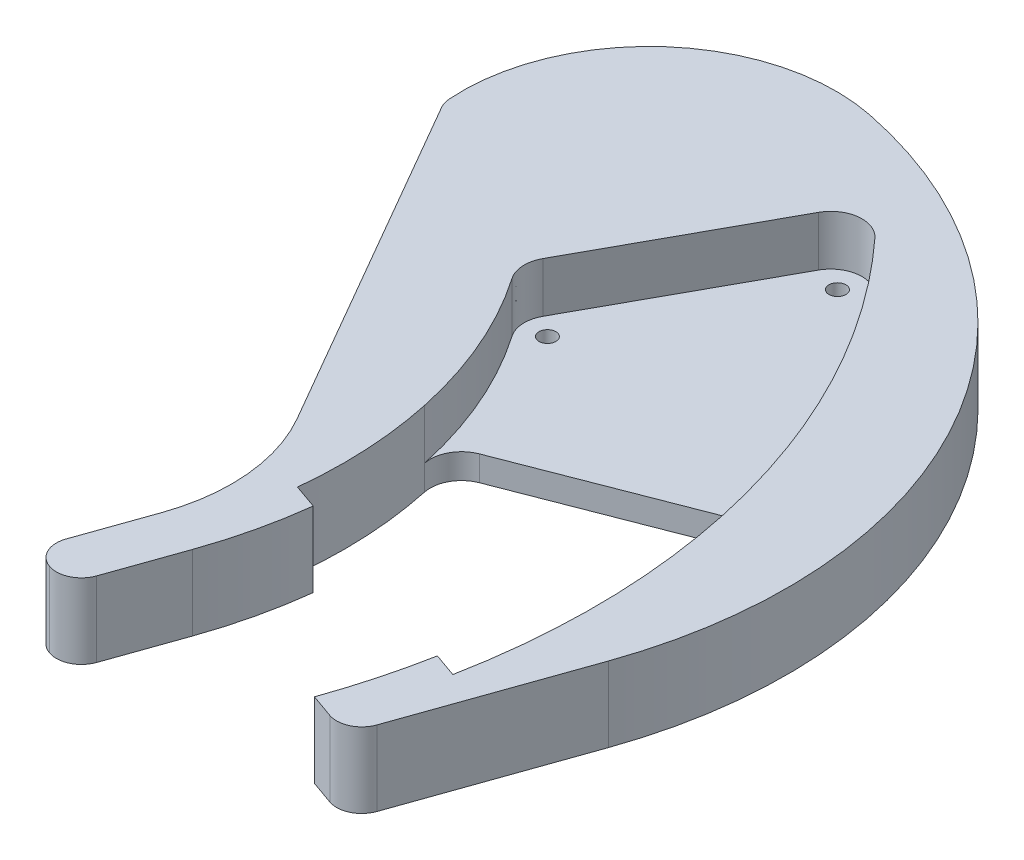
SolidWorks part; units mm, degrees
material "Pine"
ref_plane "Front Plane" through (0, 0, 0) normal (0, 0, 1) x (1, 0, 0)
ref_plane "Top Plane" through (0, 0, 0) normal (0, 1, 0) x (1, 0, 0)
ref_plane "Right Plane" through (0, 0, 0) normal (1, 0, 0) x (0, 0, -1)
sketch "Sketch1" plane through (0, 0, 0) normal (0, 1, 0) x (1, 0, 0)
  line L59 (-47.4532, 53.4043) -> (-98.2532, 141.3925)
  line L60 (0, 0) -> (27.9445, -9.8615)
  line L61 (0, 0) -> (-43.9505, 15.5099)
  line L62 (-1000, 0) -> (49000, 0) construction
  line L64 (27.9445, -9.8615) -> (72.8551, -25.7103) construction
  line L65 (72.8551, -25.7103) -> (88.7038, 19.2003) construction
  line L66 (27.9445, -9.8615) -> (-207.1917, -676.1663) construction
  line L67 (45.3803, 39.5461) -> (27.9445, -9.8615)
  line L68 (-43.9505, 15.5099) -> (-28.1017, 60.4205) construction
  line L69 (-88.861, 31.3587) -> (-86.5095, 38.0222) construction
  line L70 (53.7407, 188.0768) -> (-24.6782, 188.0768) construction
  line L71 (-43.9505, 15.5099) -> (-88.861, 31.3587) construction
  arc A0 (45.3803, 39.5461) -> (-41.5665, 192.8393) centre (-64.7226, 78.401) ccw
  arc A1 (-98.2532, 141.3925) -> (-41.5665, 192.8393) centre (-50.9898, 146.2689) cw
  arc A2 (-43.9505, 15.5099) -> (-47.4532, 53.4043) centre (-86.8603, 30.6526) ccw
  dimension "D5" = 4.7625
  dimension "D2" = 45.5033
  dimension "D11" = 37.8944
  dimension "D12" = 7.0663
  dimension "D8" = 52.3939
  dimension "D9" = 46.6069
  dimension "D4" = 19.438
  dimension "D7" = 116.7576
  dimension "D6" = 47.5143
  dimension "D10" = 29.6335
  dimension "D3" = 101.6
  dimension "D1" = 47.625
  dimension "D13" = 78.4189
extrude "Boss-Extrude1" add sketch "Sketch1" along normal blind 19.05
ref_plane "Plane1" through (-8.003, 0, -2.8242) normal (0.943, 0, 0.3328) x (0.3328, 0, -0.943)
sketch "Sketch2" plane through (0, 0, 0) normal (0, 1, 0) x (1, 0, 0)
  line L0 (-43.9505, 15.5099) -> (27.9445, -9.8615) construction
  point P2 (-8.003, 2.8242)
  point P3 (-8.003, 2.8242)
  line B0 (-29.2366, 81.4276) -> (15.5744, 98.7927)
  line B1 (11.6131, 92.147) -> (-21.6985, 79.2205)
  line B2 (-25.5648, 59.5252) -> (22.719, 42.4861)
  line B3 (28.6163, 16.8366) -> (22.5595, 18.974)
  line B4 (-26.1738, 36.1718) -> (-32.322, 38.3415)
  line B5 (-25.1489, 88.1192) -> (10.3796, 101.8872)
  line B6 (-51.3926, 119.7839) -> (-26.6046, 164.8774)
  line B7 (-44.0739, 123.2114) -> (-25.3, 157.3642)
  line B8 (-31.9553, 11.2769) -> (15.9493, -5.6285)
  line B9 (22.5595, 18.974) -> (-26.1738, 36.1718)
  arc B10 (-27.5994, 72.1341) -> (-28.8269, 77.6086) centre (-28.1238, 74.8914) ccw
  arc B11 (-29.2366, 81.4276) -> (-29.7842, 81.1914) centre (-26.3685, 74.0264) ccw
  arc B12 (17.8172, 99.3043) -> (15.5744, 98.7927) centre (18.4425, 91.3914) ccw
  arc B13 (18.8456, 95.8956) -> (20.3121, 90.5015) centre (19.3312, 93.1313) ccw
  arc B14 (13.6735, 91.1895) -> (20.9914, 87.3846) centre (19.3312, 93.1313) ccw
  arc B15 (-27.0229, 69.0118) -> (-22.587, 77.1552) centre (-28.1238, 74.8914) ccw
  arc B16 (20.3121, 90.5015) -> (18.8456, 95.8956) centre (19.3312, 93.1313) ccw
  arc B17 (28.6163, 16.8366) -> (26.1201, 93.4056) centre (-140.6727, 49.6428) ccw
  arc B18 (26.9496, 45.3998) -> (22.9664, 86.2145) centre (-140.6737, 49.643) ccw
  arc B19 (-28.827, 77.6085) -> (-27.5994, 72.1341) centre (-28.1238, 74.8914) ccw
  arc B20 (-27.6639, 62.1695) -> (-25.8173, 59.6267) centre (-24.5082, 62.5193) ccw
  arc B21 (-32.322, 38.3415) -> (-34.1314, 72.3702) centre (-140.6727, 49.6428) ccw
  arc B22 (10.3796, 101.8872) -> (14.8753, 112.2511) centre (7.5115, 109.2884) ccw
  arc B23 (-35.3684, 92.527) -> (-25.1489, 88.1192) centre (-28.017, 95.5204) ccw
  arc B24 (-43.0735, 110.8831) -> (-43.464, 121.0781) centre (-46.3902, 115.8611) ccw
  arc B25 (15.9493, -5.6285) -> (22.5595, 18.974) centre (-140.6729, 49.642) ccw
  arc B26 (-31.9553, 11.2769) -> (-26.1738, 36.1718) centre (-140.6725, 49.6436) ccw
  spline B27 degree 3 poles (17.8172, 99.3043) (18.2808, 99.3409) (18.7407, 99.3366) (19.6534, 99.2495) (20.1077, 99.1662) (21.0026, 98.9191) (21.4331, 98.7584) (22.0543, 98.4634) (22.2573, 98.356) (22.6549, 98.123) (22.8504, 97.9967) (23.4171, 97.5941) (23.7667, 97.2963) (24.2502, 96.807) (24.4045, 96.6367) (24.699, 96.2816) (24.84, 96.0958) (25.2347, 95.5249) (25.4616, 95.126) (25.8451, 94.2925) (26.0022, 93.8555) (26.1202, 93.4057) knots 0 0 0 0 0.125 0.125 0.25 0.25 0.375 0.375 0.4375 0.4375 0.5 0.5 0.625 0.625 0.6875 0.6875 0.75 0.75 0.875 0.875 1 1 1 1
  spline B28 degree 3 poles (-34.1313, 72.3702) (-34.3175, 73.2427) (-34.3554, 74.1214) (-34.1352, 75.8909) (-33.8828, 76.7344) (-33.0952, 78.3332) (-32.5797, 79.0482) (-31.6292, 79.9869) (-31.2886, 80.2706) (-30.5679, 80.7764) (-30.1868, 80.9994) (-29.7842, 81.1914) knots 0 0 0 0 0.25 0.25 0.5 0.5 0.75 0.75 0.875 0.875 1 1 1 1
  spline B29 degree 2 poles (-26.6046, 164.8774) (-26.1506, 165.7033) (-25.5154, 166.4003) (-24.879, 167.0987) (-24.0954, 167.6288) (-23.3138, 168.1575) (-22.4289, 168.4884) (-21.5475, 168.8181) (-20.6123, 168.9325) (-19.6749, 169.0473) (-18.7356, 168.9385) (-17.7973, 168.83) (-16.9097, 168.5037) (-16.0263, 168.179) (-15.2426, 167.656) (-14.4528, 167.129) (-13.8094, 166.4302) knots 0 0 0 0.125 0.125 0.25 0.25 0.375 0.375 0.5 0.5 0.625 0.625 0.75 0.75 0.875 0.875 1 1 1
  spline B30 degree 3 poles (26.1163, 93.4018) (24.3249, 100.238) (22.1302, 106.9013) (16.9621, 119.8936) (13.988, 126.2224) (9.777, 133.9217) (8.91, 135.4509) (7.1262, 138.488) (6.208, 139.9978) (3.3864, 144.4804) (1.4239, 147.3946) (-4.7015, 155.9203) (-9.1008, 161.3163) (-13.8094, 166.4302) knots 0 0 0 0 0.25 0.25 0.5 0.5 0.5625 0.5625 0.625 0.625 0.75 0.75 1 1 1 1
  spline B31 degree 3 poles (-13.3161, 158.7044) (-10.6959, 155.6457) (-8.187, 152.4937) (-4.3894, 147.3517) (-3.0295, 145.4278) (-0.3835, 141.5096) (0.9037, 139.513) (3.3926, 135.4673) (4.5925, 133.4211) (6.8969, 129.2936) (8.0024, 127.2107) (11.1817, 120.9021) (13.1195, 116.615) (14.8753, 112.2511) knots 0.074143 0.074143 0.074143 0.074143 0.222946 0.222946 0.309438 0.309438 0.395929 0.395929 0.48242 0.48242 0.568911 0.568911 0.741894 0.741894 0.741894 0.741894
  spline B32 degree 3 poles (-35.3684, 92.527) (-36.6307, 95.6269) (-38.0226, 98.6534) (-40.7885, 104.036) (-42.1249, 106.4194) (-43.5456, 108.7522) knots 0.447067 0.447067 0.447067 0.447067 0.670186 0.670186 0.854821 0.854821 0.854821 0.854821
  spline B33 degree 2 poles (-50.9715, 111.4537) (-51.5973, 112.3613) (-51.9523, 113.4056) (-52.3075, 114.4507) (-52.3641, 115.5542) (-52.4206, 116.6572) (-52.1734, 117.7348) (-51.9261, 118.8136) (-51.3926, 119.7839) knots 0 0 0 0.25 0.25 0.5 0.5 0.75 0.75 1 1 1
  spline B34 degree 3 poles (-50.9715, 111.4537) (-48.9588, 108.5346) (-47.0926, 105.5237) (-43.6539, 99.3178) (-42.0816, 96.1226) (-39.9504, 91.1875) (-39.2781, 89.5185) (-38.0214, 86.161) (-37.4355, 84.4688) (-36.3479, 81.058) (-35.8463, 79.3393) (-34.9276, 75.8754) (-34.5102, 74.1291) (-34.136, 72.3718) knots 0 0 0 0 0.25 0.25 0.5 0.5 0.625 0.625 0.75 0.75 0.875 0.875 1 1 1 1
sketch_block_instance "Ramp Geometry-1"
sketch_block "Ramp Geometry"
sketch "Sketch5" plane through (0, 19.05, 0) normal (0, 1, 0) x (1, 0, 0)
  line L1 (28.6163, 16.8366) -> (22.5595, 18.974) construction
  line L2 (-31.9553, 11.2769) -> (15.9493, -5.6285) construction
  line L3 (-26.1738, 36.1718) -> (-32.322, 38.3415) construction
  line L4 (-29.2366, 81.4276) -> (15.5744, 98.7927)
  line L5 (28.6163, 16.8366) -> (22.5595, 18.974)
  line L6 (-31.9553, 11.2769) -> (15.9493, -5.6285)
  line L7 (-26.1738, 36.1718) -> (-32.322, 38.3415)
  arc A2 (28.6163, 16.8366) -> (26.1201, 93.4056) centre (-140.6727, 49.6428) ccw construction
  arc A3 (15.9493, -5.6285) -> (22.5595, 18.974) centre (-140.6729, 49.642) ccw construction
  arc A4 (-31.9553, 11.2769) -> (-26.1738, 36.1718) centre (-140.6725, 49.6436) ccw construction
  arc A5 (-32.322, 38.3415) -> (-34.1314, 72.3702) centre (-140.6727, 49.6428) ccw construction
  arc A6 (-34.1314, 72.3702) -> (-29.2366, 81.4276) centre (-26.3759, 74.0303) cw
  arc A7 (26.1201, 93.4056) -> (15.5744, 98.7927) centre (18.4429, 91.3925) ccw
  arc A8 (28.6163, 16.8366) -> (26.1201, 93.4056) centre (-140.6727, 49.6428) ccw
  arc A9 (15.9493, -5.6285) -> (22.5595, 18.974) centre (-140.6729, 49.642) ccw
  arc A10 (-31.9553, 11.2769) -> (-26.1738, 36.1718) centre (-140.6725, 49.6436) ccw
  arc A11 (-32.322, 38.3415) -> (-34.1314, 72.3702) centre (-140.6727, 49.6428) ccw
  spline S2 degree 3 poles (17.8172, 99.3043) (18.2808, 99.3409) (18.7407, 99.3366) (19.6534, 99.2495) (20.1077, 99.1662) (21.0026, 98.9191) (21.4331, 98.7584) (22.0543, 98.4634) (22.2573, 98.356) (22.6549, 98.123) (22.8504, 97.9967) (23.4171, 97.5941) (23.7667, 97.2963) (24.2502, 96.807) (24.4045, 96.6367) (24.699, 96.2816) (24.84, 96.0958) (25.2347, 95.5249) (25.4616, 95.126) (25.8451, 94.2925) (26.0022, 93.8555) (26.1202, 93.4057) knots 0 0 0 0 0.125 0.125 0.25 0.25 0.375 0.375 0.4375 0.4375 0.5 0.5 0.625 0.625 0.6875 0.6875 0.75 0.75 0.875 0.875 1 1 1 1 construction
  spline S3 degree 3 poles (-34.1313, 72.3702) (-34.3175, 73.2427) (-34.3554, 74.1214) (-34.1352, 75.8909) (-33.8828, 76.7344) (-33.0952, 78.3332) (-32.5797, 79.0482) (-31.6292, 79.9869) (-31.2886, 80.2706) (-30.5679, 80.7764) (-30.1868, 80.9994) (-29.7842, 81.1914) knots 0 0 0 0 0.25 0.25 0.5 0.5 0.75 0.75 0.875 0.875 1 1 1 1 construction
extrude "Cut-Extrude1" cut sketch "Sketch5" against normal through all
sketch "Sketch7" plane through (0, 0, 0) normal (0, 1, 0) x (1, 0, 0)
  line L0 (-43.9505, 15.5099) -> (-52.4031, -8.4424)
  line L1 (-52.4031, -8.4424) -> (-40.4081, -12.6754)
  line L2 (-40.4081, -12.6754) -> (-31.9553, 11.2769)
  line L3 (-31.9553, 11.2769) -> (-43.9505, 15.5099)
  arc A0 (-31.9553, 11.2769) -> (-26.1738, 36.1718) centre (-140.6725, 49.6436) ccw construction
  arc A1 (-43.9505, 15.5099) -> (-47.4532, 53.4043) centre (-86.8603, 30.6526) ccw construction
  dimension "D1" = 25.4
extrude "Boss-Extrude2" add sketch "Sketch7" along normal up to surface (19.05 mm away) up to face at (-10.6552, 19.05, -58.2825)
fillet "Fillet1" radius 6.35 4 edges at (-98.2532, 9.525, -141.3925) (27.9445, 9.525, 9.8615) (-40.4081, 9.525, 12.6754) (-52.4031, 9.525, 8.4424)
sketch "Sketch6" plane through (0, 19.05, 0) normal (0, 1, 0) x (1, 0, 0)
  line L0 (-34.136, 72.3718) -> (26.1163, 93.4018)
  line L2 (-51.3926, 119.7839) -> (-26.6046, 164.8774) construction
  line L3 (-51.3926, 119.7839) -> (-26.6046, 164.8774)
  spline S0 degree 3 poles (-1429.6439, -1247.1312) (-221.2393, -482.3872) (103.2117, -96.9361) (16.9621, 119.8936) (13.988, 126.2224) (9.777, 133.9217) (8.91, 135.4509) (7.1262, 138.488) (6.208, 139.9978) (3.3864, 144.4804) (1.4239, 147.3946) (-186.5695, 409.0534) (-1027.0588, 71.2021) (-1932.3264, -325.7002) knots -7.844512 -7.844512 -7.844512 -7.844512 0.25 0.25 0.5 0.5 0.5625 0.5625 0.625 0.625 0.75 0.75 12.134027 12.134027 12.134027 12.134027 only from (26.1163, 93.4018) to (-13.8094, 166.4302) construction
  spline S1 degree 2 poles (1493.7423, -1132.5068) (-85.9486, 100.0778) (-25.5154, 166.4003) (-24.879, 167.0987) (-24.0954, 167.6288) (-23.3138, 168.1575) (-22.4289, 168.4884) (-21.5475, 168.8181) (-20.6123, 168.9325) (-19.6749, 169.0473) (-18.7356, 168.9385) (-17.7973, 168.83) (-16.9097, 168.5037) (-16.0263, 168.179) (-15.2426, 167.656) (59.3198, 117.902) (-1170.3473, -1463.6448) knots -11.768568 -11.768568 -11.768568 0.125 0.125 0.25 0.25 0.375 0.375 0.5 0.5 0.625 0.625 0.75 0.75 0.875 0.875 12.67723 12.67723 12.67723 only from (-26.6046, 164.8774) to (-13.8094, 166.4302) construction
  spline S2 degree 2 poles (1805.4899, 851.8486) (-23.0142, 28.2719) (-51.9523, 113.4056) (-52.3075, 114.4507) (-52.3641, 115.5542) (-52.4206, 116.6572) (-52.1734, 117.7348) (-32.0934, 205.297) (1872.6772, -421.0496) knots -20.129916 -20.129916 -20.129916 0.25 0.25 0.5 0.5 0.75 0.75 21.042954 21.042954 21.042954 only from (-50.9715, 111.4537) to (-51.3926, 119.7839) construction
  spline S3 degree 3 poles (-1984.765, -331.989) (-829.3418, 131.8338) (-152.4686, 295.6978) (-43.6539, 99.3178) (-42.0816, 96.1226) (-39.9504, 91.1875) (-39.2781, 89.5185) (-38.0214, 86.161) (-37.4355, 84.4688) (-36.3479, 81.058) (-35.8463, 79.3393) (3.3124, -68.2971) (-256.1389, -315.9435) (-1530.5486, 1352.6355) knots -15.321981 -15.321981 -15.321981 -15.321981 0.25 0.25 0.5 0.5 0.625 0.625 0.75 0.75 0.875 0.875 11.405236 11.405236 11.405236 11.405236 only from (-50.9715, 111.4537) to (-34.136, 72.3718) construction
  spline S4 degree 3 poles (26.1163, 93.4018) (24.3249, 100.238) (22.1302, 106.9013) (16.9621, 119.8936) (13.988, 126.2224) (9.777, 133.9217) (8.91, 135.4509) (7.1262, 138.488) (6.208, 139.9978) (3.3864, 144.4804) (1.4239, 147.3946) (-4.7015, 155.9203) (-9.1008, 161.3163) (-13.8094, 166.4302) knots 0 0 0 0 0.25 0.25 0.5 0.5 0.5625 0.5625 0.625 0.625 0.75 0.75 1 1 1 1
  spline S5 degree 2 poles (-26.6046, 164.8774) (-26.1506, 165.7033) (-25.5154, 166.4003) (-24.879, 167.0987) (-24.0954, 167.6288) (-23.3138, 168.1575) (-22.4289, 168.4884) (-21.5475, 168.8181) (-20.6123, 168.9325) (-19.6749, 169.0473) (-18.7356, 168.9385) (-17.7973, 168.83) (-16.9097, 168.5037) (-16.0263, 168.179) (-15.2426, 167.656) (-14.4528, 167.129) (-13.8094, 166.4302) knots 0 0 0 0.125 0.125 0.25 0.25 0.375 0.375 0.5 0.5 0.625 0.625 0.75 0.75 0.875 0.875 1 1 1
  spline S6 degree 2 poles (-50.9715, 111.4537) (-51.5973, 112.3613) (-51.9523, 113.4056) (-52.3075, 114.4507) (-52.3641, 115.5542) (-52.4206, 116.6572) (-52.1734, 117.7348) (-51.9261, 118.8136) (-51.3926, 119.7839) knots 0 0 0 0.25 0.25 0.5 0.5 0.75 0.75 1 1 1
  spline S7 degree 3 poles (-50.9715, 111.4537) (-48.9588, 108.5346) (-47.0926, 105.5237) (-43.6539, 99.3178) (-42.0816, 96.1226) (-39.9504, 91.1875) (-39.2781, 89.5185) (-38.0214, 86.161) (-37.4355, 84.4688) (-36.3479, 81.058) (-35.8463, 79.3393) (-34.9276, 75.8754) (-34.5102, 74.1291) (-34.136, 72.3718) knots 0 0 0 0 0.25 0.25 0.5 0.5 0.625 0.625 0.75 0.75 0.875 0.875 1 1 1 1
extrude "Cut-Extrude2" cut sketch "Sketch6" against normal blind 12.7
hole_wizard "#8 Clearance Hole1" positions "Sketch8" profile "Sketch9" hole size "#8" standard "ANSI Inch" end condition through all
sketch "Sketch8" plane through (0, 0, 0) normal (0, -1, 0) x (-1, 0, 0)
  line L0 (46.3904, 115.861) -> (19.8844, 162.9953) construction
  line L2 (19.8844, 162.9953) -> (13.8094, 166.4302) construction
  line L5 (46.3904, 115.861) -> (50.9715, 111.4537) construction
  spline S0 degree 2 poles (13.8094, 166.4302) (14.4528, 167.129) (15.2426, 167.656) (16.0263, 168.179) (16.9097, 168.5037) (17.7973, 168.83) (18.7356, 168.9385) (19.6749, 169.0473) (20.6123, 168.9325) (21.5475, 168.8181) (22.4289, 168.4884) (23.3138, 168.1575) (24.0954, 167.6288) (24.879, 167.0987) (25.5154, 166.4003) (26.1506, 165.7033) (26.6046, 164.8774) knots 0 0 0 0.125 0.125 0.25 0.25 0.375 0.375 0.5 0.5 0.625 0.625 0.75 0.75 0.875 0.875 1 1 1 construction
  spline S1 degree 3 poles (-26.0451, 93.6725) (-24.2669, 100.414) (-22.096, 106.987) (-16.9621, 119.8936) (-13.988, 126.2224) (-9.777, 133.9217) (-8.91, 135.4509) (-7.1262, 138.488) (-6.208, 139.9978) (-3.3864, 144.4804) (-1.4239, 147.3946) (4.7015, 155.9203) (9.1008, 161.3163) (13.8094, 166.4302) knots 0.003301 0.003301 0.003301 0.003301 0.25 0.25 0.5 0.5 0.5625 0.5625 0.625 0.625 0.75 0.75 1 1 1 1 construction
  spline S2 degree 2 poles (51.3926, 119.7839) (51.9261, 118.8136) (52.1734, 117.7348) (52.4206, 116.6572) (52.3641, 115.5542) (52.3075, 114.4507) (51.9523, 113.4056) (51.5973, 112.3613) (50.9715, 111.4537) knots 0 0 0 0.25 0.25 0.5 0.5 0.75 0.75 1 1 1 construction
  point P0 (46.3904, 115.861)
  point P2 (19.8844, 162.9953)
  dimension "D1" = 54.0759
  dimension "D2" = 6.357
  dimension "D3" = 6.9788
  dimension "D4" = 148.836
  dimension "D5" = 163.244
sketch "Sketch9" plane through (-46.3904, 0, -115.861) normal (1, 0, 0) x (0, 0, -1)
  line L0 (0, 0) -> (0, 19.05)
  line L1 (0, 19.05) -> (2.1526, 19.05)
  line L2 (2.1526, 19.05) -> (2.1526, 0)
  line L5 (2.1526, 0) -> (0, 0)
  line L11 (0, -6.35) -> (0, 107.95) construction
  dimension "Thru Hole Dia." = 4.3053
  dimension "Thru Hole Depth" = 19.05
sketch "Sketch10" plane through (0, 0, 0) normal (0, -1, 0) x (1, 0, 0)
  line L0 (54.184, -189.0962) -> (-27.589, -189.0962)
  arc A0 (-41.5665, -192.8393) -> (45.3803, -39.5461) centre (-64.7226, -78.401) ccw construction
  dimension "D1" = 81.773
  dimension "D2" = 189.0962
